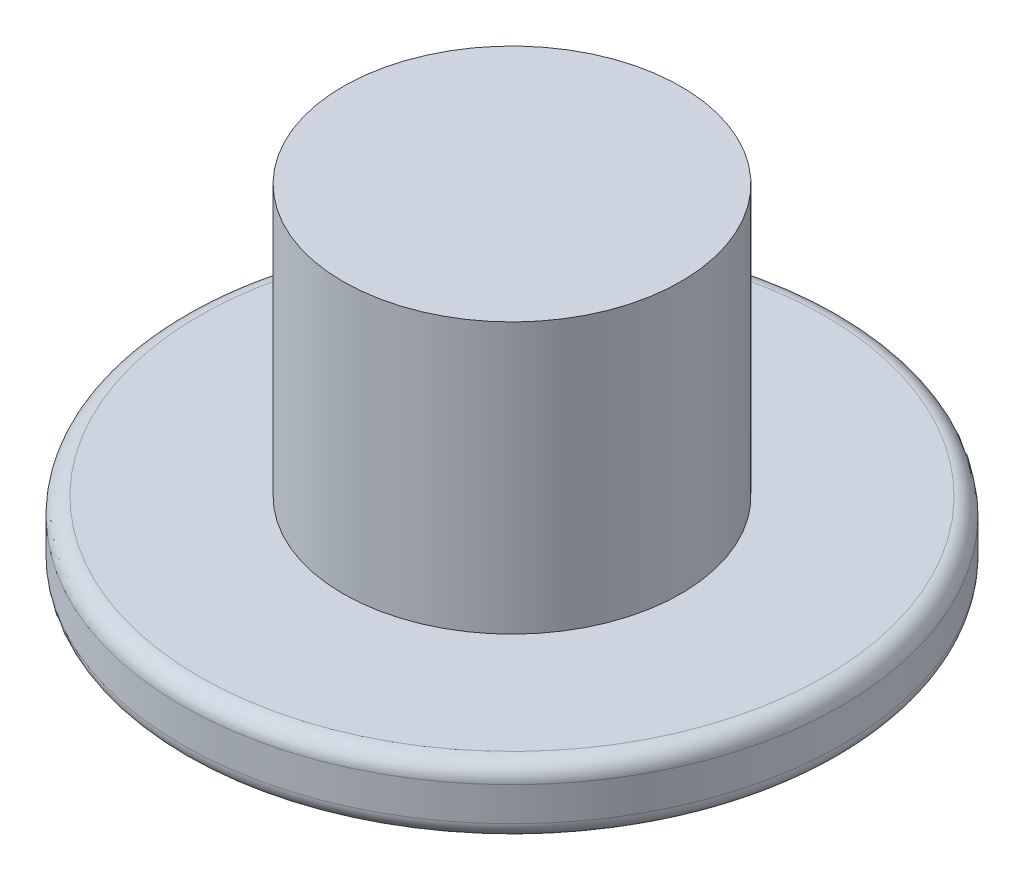
SolidWorks part; units mm, degrees
ref_plane "Front Plane" through (0, 0, 0) normal (0, 0, 1) x (1, 0, 0)
ref_plane "Top Plane" through (0, 0, 0) normal (0, 1, 0) x (1, 0, 0)
ref_plane "Right Plane" through (0, 0, 0) normal (1, 0, 0) x (0, 0, -1)
sketch "Sketch1" plane through (0, 0, 0) normal (0, 1, 0) x (1, 0, 0)
  circle A4 centre (-5.4087, -40.3067) radius 9.75
  circle A12 centre (-5.4087, -40.3067) radius 4.9321
  dimension "D5" = 19.5
extrude "Boss-Extrude5" add sketch "Sketch1" along normal blind 2 contours A4
sketch "Sketch4" plane through (0, 2, 0) normal (0, 1, 0) x (1, 0, 0)
  circle A0 centre (-5.4087, -40.3067) radius 5
  circle A1 centre (-5.4087, -40.3067) radius 9.75 construction
extrude "Boss-Extrude6" add sketch "Sketch4" along normal blind 8
sketch "Sketch5" plane through (0, 0, 0) normal (0, -1, 0) x (1, 0, 0)
  text T0 "2" font "Century Gothic" height 9
  point P1 (-5.4087, 25.1919)
  point P2 (0, 0)
extrude "Cut-Extrude2" cut sketch "Sketch5" against normal blind 0.5
fillet "Fillet1" radius 0.5 2 edges at (-5.4087, 2, 50.0567) (-5.4087, 0, 50.0567)
